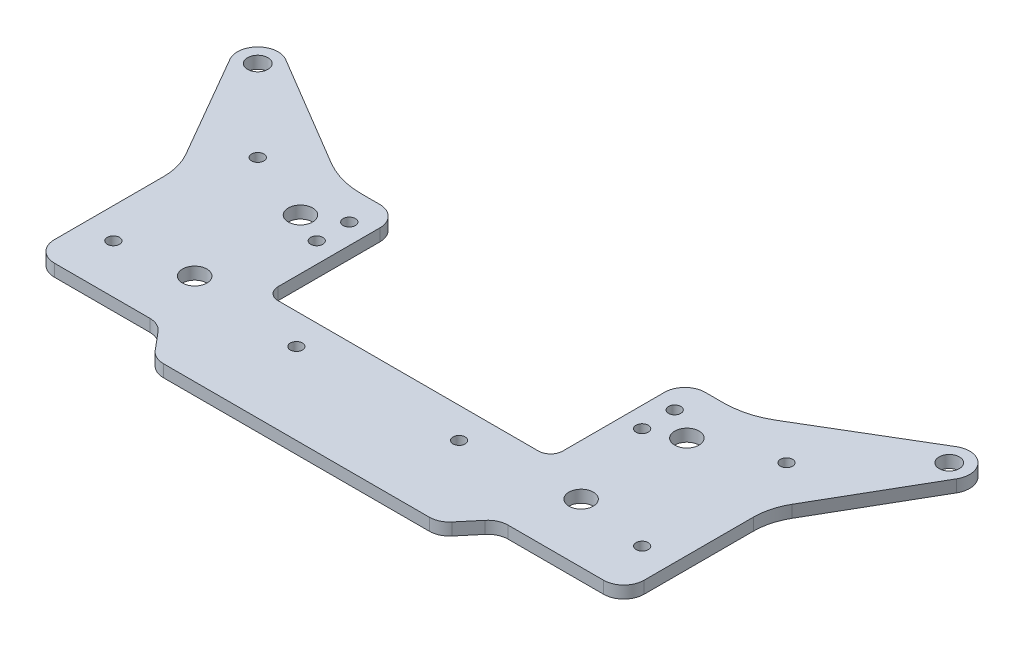
SolidWorks part; units mm, degrees
material "Thornel Mat VMA"
ref_plane "前视基准面" through (0, 0, 0) normal (0, 0, 1) x (1, 0, 0)
ref_plane "上视基准面" through (0, 0, 0) normal (0, 1, 0) x (1, 0, 0)
ref_plane "右视基准面" through (0, 0, 0) normal (1, 0, 0) x (0, 0, -1)
sketch "草图1" plane through (0, 0, 0) normal (0, 1, 0) x (1, 0, 0)
  line L0 (-85, 0) -> (85, 0) construction
  line L1 (0, 0) -> (0, -55.5) construction
  line L2 (-65, -55.5) -> (65, -55.5) construction
  line L3 (-35, -15) -> (-35, -45)
  line L4 (-32, -48) -> (32, -48)
  line L5 (35, -45) -> (35, -15)
  line L6 (35, -15) -> (50, -15)
  line L7 (40, -30.5) -> (40, -22.5) construction
  line L9 (72.5, -67.5) -> (41.7128, -67.5)
  line L10 (41.7128, -67.5) -> (35, -75.5)
  line L11 (35, -75.5) -> (-35, -75.5)
  line L12 (-35, -75.5) -> (-41.7128, -67.5)
  line L13 (-41.7128, -67.5) -> (-72.5, -67.5)
  line L14 (-72.5, -67.5) -> (-72.5, -35.6699)
  line L15 (-74.5096, -28.1699) -> (-89.3301, -2.5)
  line L16 (72.5, -67.5) -> (72.5, -35.6699)
  line L17 (74.5096, -28.1699) -> (89.3301, -2.5)
  line L18 (-82.444, 4.2973) -> (-50, -15)
  line L19 (-50, -15) -> (-35, -15)
  line L20 (50, -15) -> (82.444, 4.2973)
  circle A0 centre (85, 0) radius 2.5
  circle A1 centre (-85, 0) radius 2.5
  arc A2 (-82.444, 4.2973) -> (-89.3301, -2.5) centre (-85, 0) ccw
  arc A3 (89.3301, -2.5) -> (82.444, 4.2973) centre (85, 0) ccw
  arc A4 (-35, -45) -> (-32, -48) centre (-32, -45) ccw
  circle A5 centre (47.5, -53) radius 3
  circle A6 centre (-47.5, -53) radius 3
  arc A7 (32, -48) -> (35, -45) centre (32, -45) ccw
  circle A8 centre (20, -55.5) radius 1.5
  circle A9 centre (-20, -55.5) radius 1.5
  circle A10 centre (-65, -55.5) radius 1.5
  circle A11 centre (65, -55.5) radius 1.5
  arc A12 (72.5, -35.6699) -> (74.5096, -28.1699) centre (87.5, -35.6699) cw
  arc A13 (-72.5, -35.6699) -> (-74.5096, -28.1699) centre (-87.5, -35.6699) ccw
  circle A14 centre (65, -20) radius 1.5
  circle A15 centre (-65, -20) radius 1.5
  circle A16 centre (40, -22.5) radius 1.5
  circle A17 centre (40, -30.5) radius 1.5
  circle A18 centre (-47.5, -27) radius 3
  circle A19 centre (47.5, -27) radius 3
  circle A20 centre (-40, -30.5) radius 1.5
  circle A21 centre (-40, -22.5) radius 1.5
  point P14 (-35, -48)
  point P44 (40, -26.5)
  point P45 (0, -75.5)
  point P55 (35, -48)
  dimension "D2" = 10
  dimension "D3" = 5
  dimension "D5" = 20
  dimension "D8" = 40
  dimension "D9" = 45
  dimension "D10" = 3
  dimension "D14" = 15
  dimension "D19" = 3
  dimension "D20" = 20
  dimension "D21" = 20
  dimension "D22" = 21.5
  dimension "D25" = 15
  dimension "D16" = 26
  dimension "D17" = 5
  dimension "D23" = 5
  dimension "D24" = 8
  dimension "D27" = 3
  dimension "D28" = 3
  dimension "D29" = 95
  dimension "D30" = 6
  dimension "D1" = 170
  dimension "D4" = 70
  dimension "D6" = 7.5
  dimension "D7" = 55.5
  dimension "D11" = 12
  dimension "D12" = 145
  dimension "D13" = 60
  dimension "D15" = 70
  dimension "D18" = 100
  dimension "D26" = 130
extrude "凸台-拉伸1" add sketch "草图1" along normal blind 3
fillet "圆角1" radius 20 2 edges at (50, 1.5, 15) (-50, 1.5, 15)
fillet "圆角2" radius 5 8 edges at (-41.7128, 1.5, 67.5) (35, 1.5, 75.5) (41.7128, 1.5, 67.5) (-35, 1.5, 75.5) (35, 1.5, 15) (-35, 1.5, 15) (72.5, 1.5, 67.5) (-72.5, 1.5, 67.5)
